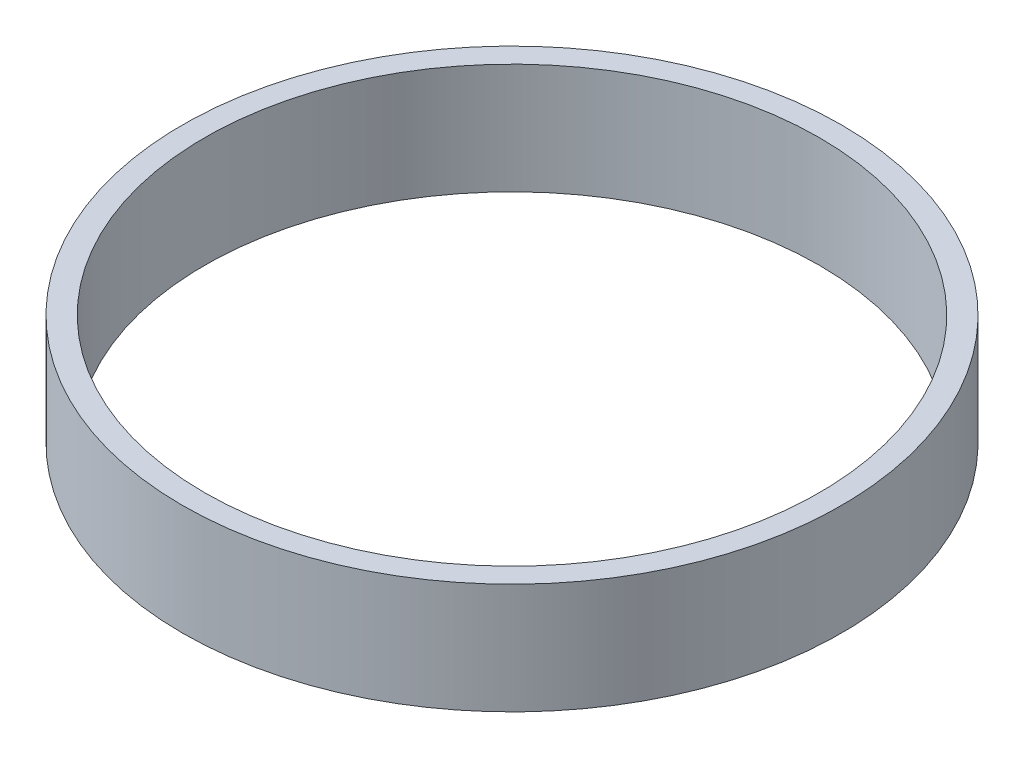
SolidWorks part; units mm, degrees
ref_plane "Front Plane" through (0, 0, 0) normal (0, 0, 1) x (1, 0, 0)
ref_plane "Top Plane" through (0, 0, 0) normal (0, 1, 0) x (1, 0, 0)
ref_plane "Right Plane" through (0, 0, 0) normal (1, 0, 0) x (0, 0, -1)
sketch "Sketch4" plane through (0, 0, 0) normal (0, 1, 0) x (1, 0, 0)
  line L0 (127.2149, 12.3898) -> (129.2149, 12.3898) construction
  circle A1 centre (99.4149, 12.3898) radius 27.8
  circle A2 centre (99.4149, 12.3898) radius 29.8
  dimension "D1" = 55.6
  dimension "D2" = 2
extrude "Boss-Extrude1" add sketch "Sketch4" along normal blind 10 separate body
